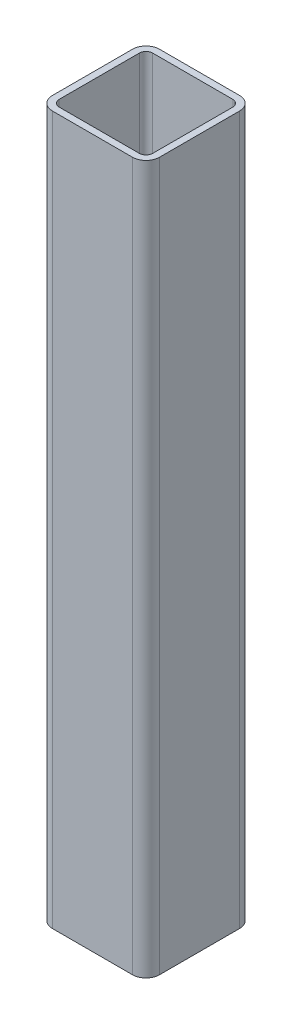
SolidWorks part; units mm, degrees
ref_plane "Front Plane" through (0, 0, 0) normal (0, 0, 1) x (1, 0, 0)
ref_plane "Top Plane" through (0, 0, 0) normal (0, 1, 0) x (1, 0, 0)
ref_plane "Right Plane" through (0, 0, 0) normal (1, 0, 0) x (0, 0, -1)
sketch3d "3DSketch2"
  line L0 (0, 0, 0) -> (0, 210, 0)
  dimension "D1" = 210
other "Square tube 20 X 20 X 2(3)"
ref_plane "Plane3" through (0, 0, 0) normal (0, 1, 0) x (1, 0, 0)
sketch "Sketch1" plane through (0, 0, 0) normal (0, 1, 0) x (1, 0, 0)
  line L0 (-11.875, -13.875) -> (11.875, -13.875)
  line L1 (-13.875, -11.875) -> (-13.875, 11.875)
  line L2 (11.875, 13.875) -> (-11.875, 13.875)
  line L3 (13.875, 11.875) -> (13.875, -11.875)
  line L4 (-11.875, -15.875) -> (11.875, -15.875)
  line L5 (-15.875, -11.875) -> (-15.875, 11.875)
  line L6 (11.875, 15.875) -> (-11.875, 15.875)
  line L7 (15.875, 11.875) -> (15.875, -11.875)
  arc A0 (15.875, 11.875) -> (11.875, 15.875) centre (11.875, 11.875) ccw
  arc A1 (11.875, -15.875) -> (15.875, -11.875) centre (11.875, -11.875) ccw
  arc A2 (-15.875, -11.875) -> (-11.875, -15.875) centre (-11.875, -11.875) ccw
  arc A3 (-11.875, 15.875) -> (-15.875, 11.875) centre (-11.875, 11.875) ccw
  arc A4 (-11.875, 13.875) -> (-13.875, 11.875) centre (-11.875, 11.875) ccw
  arc A5 (13.875, 11.875) -> (11.875, 13.875) centre (11.875, 11.875) ccw
  arc A6 (11.875, -13.875) -> (13.875, -11.875) centre (11.875, -11.875) ccw
  arc A7 (-13.875, -11.875) -> (-11.875, -13.875) centre (-11.875, -11.875) ccw
  point P0 (-15.875, 0)
  point P1 (15.875, 0)
  point P2 (0, 15.875)
  point P3 (0, -15.875)
  point P4 (0, 0)
  point P5 (-15.875, -15.875)
  point P6 (15.875, -15.875)
  point P7 (15.875, 15.875)
  point P8 (-15.875, 15.875)
  point P33 (0, 0)
  dimension "D1" = 4
  dimension "Thickness" = 2
  dimension "V_leg" = 31.75
